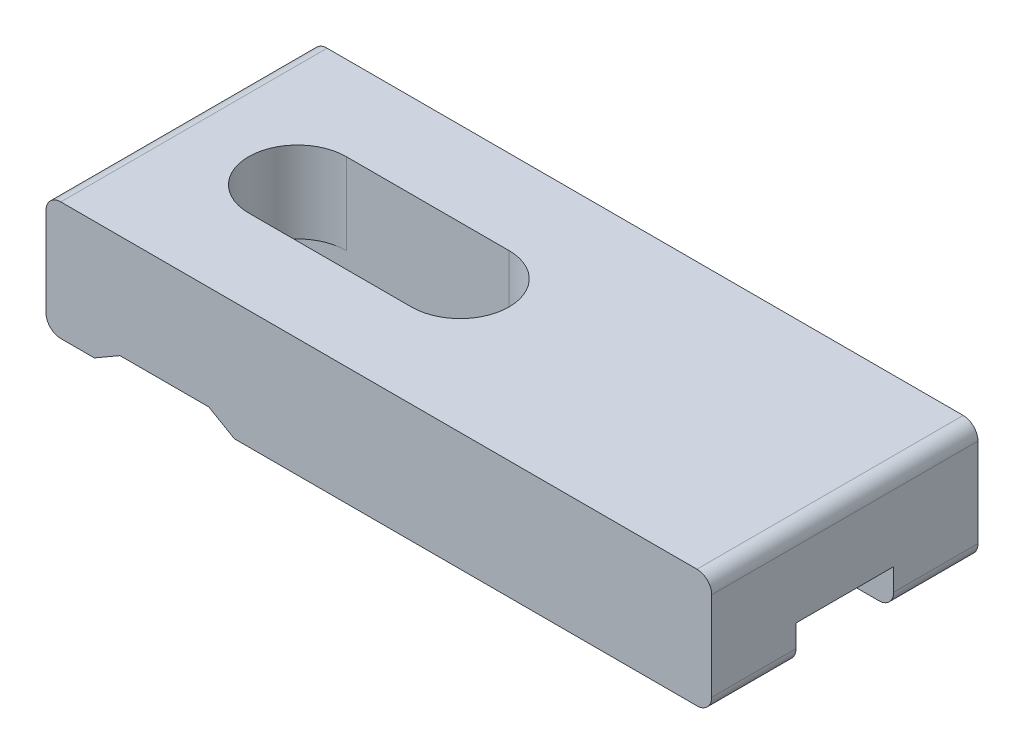
SolidWorks part; units mm, degrees
ref_plane "前视基准面" through (0, 0, 0) normal (0, 0, 1) x (1, 0, 0)
ref_plane "上视基准面" through (0, 0, 0) normal (0, 1, 0) x (1, 0, 0)
ref_plane "右视基准面" through (0, 0, 0) normal (1, 0, 0) x (0, 0, -1)
sketch "草图1" plane through (0, 0, 0) normal (0, 0, 1) x (1, 0, 0)
  line L0 (-22.5, 0) -> (22.5, 0)
  line L3 (22.5, 0) -> (22.5, 8)
  line L4 (22.5, 8) -> (-22.5, 8)
  line L5 (-22.5, 8) -> (-22.5, 0)
  dimension "D1" = 8
  dimension "D4" = 45
extrude "凸台-拉伸1" add sketch "草图1" along normal mid plane 18
sketch "草图2" plane through (0, 8, 0) normal (0, 1, 0) x (1, 0, 0)
  line L0 (-14.5, 3.3) -> (-3.5, 3.3)
  line L1 (-3.5, -3.3) -> (-14.5, -3.3)
  line L2 (-22.5, -9) -> (-22.5, 9) construction
  arc A0 (-3.5, 3.3) -> (-3.5, -3.3) centre (-3.5, 0) cw
  arc A1 (-14.5, -3.3) -> (-14.5, 3.3) centre (-14.5, 0) cw
  point P6 (-22.5, 0)
  dimension "D1" = 6.6
  dimension "D2" = 19
  dimension "D3" = 11
extrude "切除-拉伸1" cut sketch "草图2" against normal through all
sketch "草图4" plane through (22.5, 0, 0) normal (1, 0, 0) x (0, 0, -1)
  line L0 (-9, 0) -> (9, 0) construction
  line L2 (3.3, 0) -> (-3.3, 0)
  line L3 (3.3, 0) -> (3.3, 2.5)
  line L4 (3.3, 2.5) -> (-3.3, 2.5)
  line L5 (-3.3, 0) -> (-3.3, 2.5)
  dimension "D1" = 6.6
  dimension "D2" = 3.3
  dimension "D3" = 2.5
extrude "切除-拉伸2" cut sketch "草图4" against normal through all
sketch "草图5" plane through (0, 0, 9) normal (0, 0, 1) x (1, 0, 0)
  line L0 (-17.5, 1) -> (-11.5, 1)
  line L1 (-11.5, 1) -> (-9.7679, 0)
  line L2 (-22.5, 0) -> (22.5, 0) construction
  line L3 (-9.7679, 0) -> (-19.2321, 0)
  line L4 (-19.2321, 0) -> (-17.5, 1)
  line L5 (-22.5, 8) -> (-22.5, 0) construction
  dimension "D1" = 30
  dimension "D2" = 30
  dimension "D3" = 1
  dimension "D4" = 6
  dimension "D5" = 5
extrude "切除-拉伸3" cut sketch "草图5" against normal through all
fillet "圆角1" radius 1 6 edges at (-22.5, 0, -6.15) (-22.5, 0, 6.15) (22.5, 0, -6.15) (22.5, 0, 6.15) (22.5, 8, 0) (-22.5, 8, 0)
scale "缩放比例1" scale about centroid uniform scaling yes scale factor 2.666667
